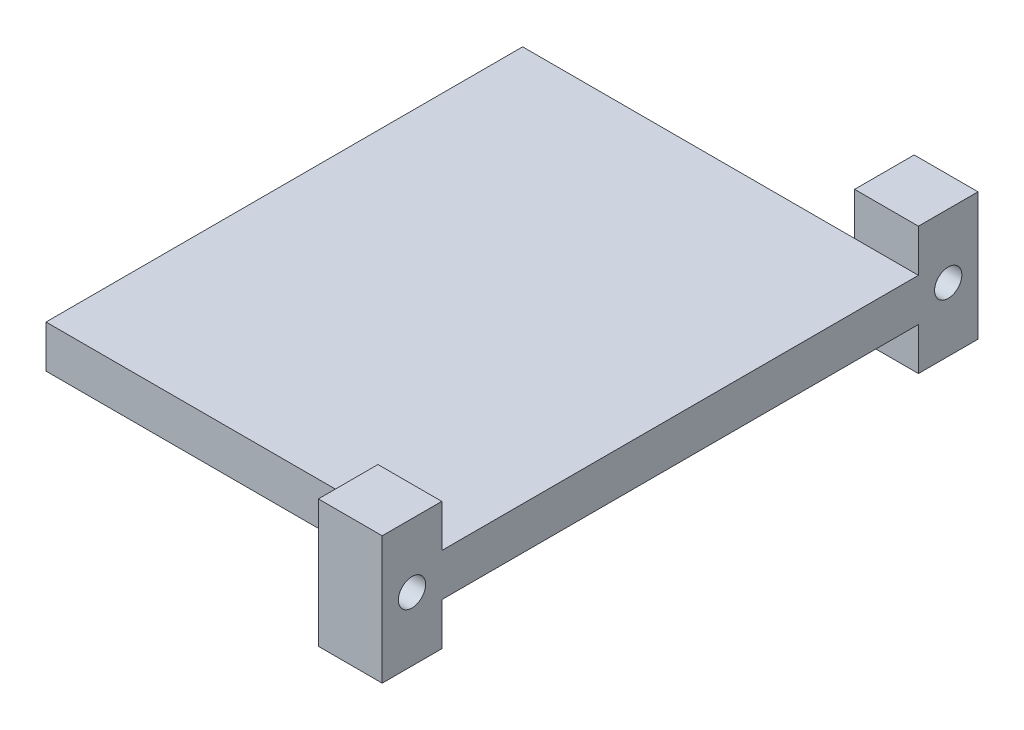
SolidWorks part; units mm, degrees
ref_plane "前视基准面" through (0, 0, 0) normal (0, 0, 1) x (1, 0, 0)
ref_plane "上视基准面" through (0, 0, 0) normal (0, 1, 0) x (1, 0, 0)
ref_plane "右视基准面" through (0, 0, 0) normal (1, 0, 0) x (0, 0, -1)
sketch "草图1" plane through (0, 0, 0) normal (0, 1, 0) x (1, 0, 0)
  line L0 (0, 0) -> (0, -100)
  line L1 (0, -100) -> (100, -100)
  line L2 (100, -100) -> (100, 0)
  line L3 (0, 0) -> (100, 0)
extrude "凸台-拉伸1" add sketch "草图1" along normal blind 5 contours L3 L2 L1 L0
sketch "草图2" plane through (0, 0, 0) normal (-1, 0, 0) x (0, 0, 1)
  line L0 (30, 0) -> (30, 5)
  line L1 (0, 0) -> (100, 0) construction
  line L2 (20, 0) -> (110, 0) construction
  line L3 (0, 5) -> (100, 5) construction
  line L4 (110, 5) -> (20, 5) construction
  line L5 (30, 5) -> (0, 5)
  line L6 (0, 5) -> (0, 0)
  line L7 (0, 0) -> (30, 0)
extrude "切除-拉伸1" cut sketch "草图2" against normal up to vertex (100 mm away) up to point (100, 0, 0)
sketch "草图3" plane through (0, 0, 0) normal (0, -1, 0) x (1, 0, 0)
  line L0 (59.25, 43.5) -> (55.5, 43.5)
  line L1 (55.5, 43.5) -> (53.5, 43.5)
  line L2 (53.5, 43.5) -> (53.5, 30)
  line L3 (100, 30) -> (0, 30) construction
  line L4 (53.5, 30) -> (0, 30)
  line L5 (0, 30) -> (0, 100)
  line L6 (0, 100) -> (53.5, 100)
  line L7 (0, 100) -> (100, 100) construction
  line L8 (53.5, 100) -> (53.5, 43.5)
  arc A0 (59.25, 47.25) -> (59.25, 39.75) centre (59.25, 43.5) ccw construction
extrude "切除-拉伸2" cut sketch "草图3" against normal up to vertex (5 mm away) contours L2 L4 L5 L6 L8 up to point (0, 5, 30)
sketch "草图4" plane through (0, 0, 0) normal (0, -1, 0) x (1, 0, 0)
  line L0 (92.5, 37) -> (92.5, 30)
  line L1 (100, 30) -> (53.5, 30) construction
  line L2 (92.5, 37) -> (92.5, 100)
  line L3 (53.5, 100) -> (100, 100) construction
  line L4 (53.5, 37) -> (92.5, 37)
  line L5 (53.5, 100) -> (53.5, 30) construction
  line L6 (53.5, 30) -> (53.5, 37)
  line L7 (53.5, 30) -> (92.5, 30)
  line L8 (92.5, 93) -> (53.5, 93)
  line L9 (53.5, 93) -> (53.5, 100)
  line L10 (53.5, 100) -> (92.5, 100)
  line M1 (53.5, 100) -> (53.5, 30)
  line M2 (53.5, 30) -> (100, 30)
  line M4 (100, 100) -> (53.5, 100)
extrude "切除-拉伸3" cut sketch "草图4" against normal up to vertex (5 mm away) contours L4 L0 M1 M2 | L8 L2 M4 M1
sketch "草图5" plane through (0, 0, 30) normal (0, 0, -1) x (-1, 0, 0)
  line L0 (-92.5, 5) -> (-92.5, 10)
  line L1 (-92.5, 10) -> (-100, 10)
  line L2 (-100, -41.829) -> (-100, 279.4539) construction
  line L3 (-100, 10) -> (-100, 5)
  line L4 (-100, 5) -> (-92.5, 5)
extrude "凸台-拉伸2" add sketch "草图5" against normal up to vertex (70 mm away) up to point (92.5, 5, 100)
sketch "草图6" plane through (92.5, 0, 0) normal (-1, 0, 0) x (0, 0, 1)
  line L0 (37, 5) -> (37, 10)
  line L1 (100, 10) -> (30, 10) construction
  line L2 (37, 10) -> (93, 10)
  line L3 (93, 10) -> (93, 5)
  line L4 (93, 5) -> (37, 5)
extrude "切除-拉伸5" cut sketch "草图6" against normal up to vertex (7.5 mm away) contours L4 L0 L2 L3
sketch "草图7" plane through (92.5, 0, 0) normal (-1, 0, 0) x (0, 0, 1)
  line L0 (30, 0) -> (30, -5)
  line L1 (30, -10) -> (30, 250) construction
  line L2 (30, -5) -> (37, -5)
  line L3 (37, -7.2) -> (37, 0) construction
  line L4 (37, -5) -> (37, 0)
  line L5 (37, 0) -> (30, 0)
  line L6 (93, 0) -> (93, -5)
  line L7 (93, -7.2) -> (93, 0) construction
  line L8 (93, -5) -> (100, -5)
  line L9 (100, 250) -> (100, -10) construction
  line L10 (100, -5) -> (100, 0)
  line L11 (100, 0) -> (93, 0)
extrude "凸台-拉伸3" add sketch "草图7" against normal up to vertex (7.5 mm away) up to point (100, 0, 100)
sketch "草图8" plane through (92.5, 0, 0) normal (-1, 0, 0) x (0, 0, 1)
  line L0 (93, 5) -> (100, 0)
  line L1 (100, 10) -> (100, -5) construction
  line L2 (37, 0) -> (30, 5)
  line L3 (30, 10) -> (30, -5) construction
  circle A0 centre (96.5, 2.5) radius 1.6
  circle A1 centre (33.5, 2.5) radius 1.6
extrude "切除-拉伸6" cut sketch "草图8" against normal up to vertex (7.5 mm away) contours L2 A1 | L2 A1 | L0 A0 | L0 A0 up to point (100, 10, 37)
